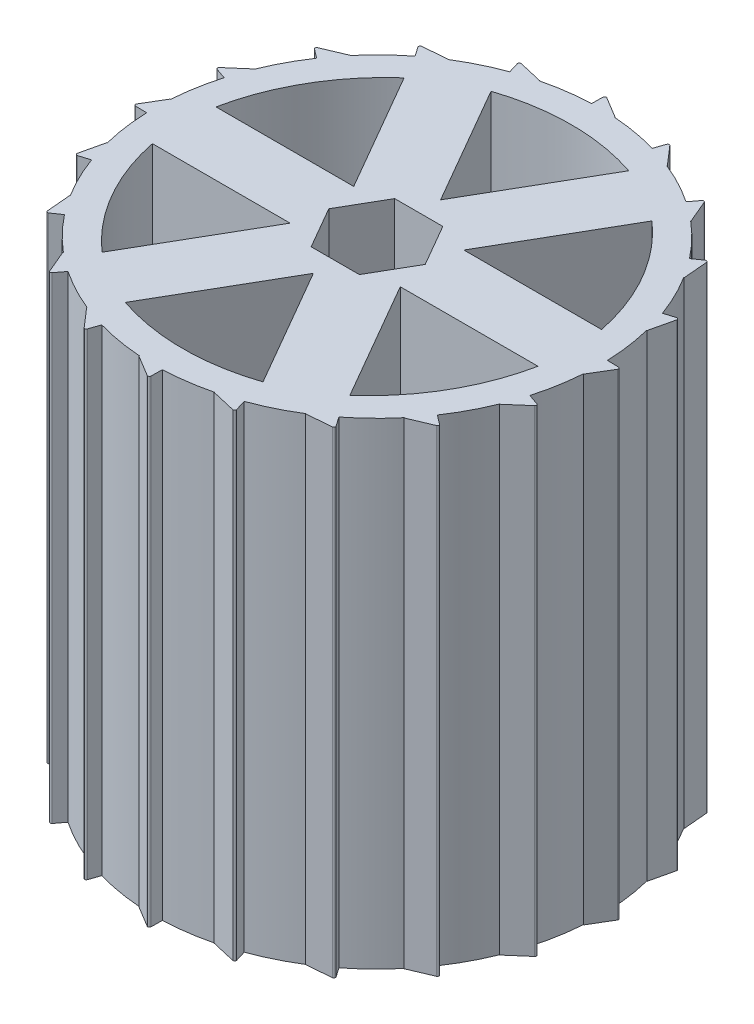
SolidWorks part; units mm, degrees
ref_plane "Front Plane" through (0, 0, 0) normal (0, 0, 1) x (1, 0, 0)
ref_plane "Top Plane" through (0, 0, 0) normal (0, 1, 0) x (1, 0, 0)
ref_plane "Right Plane" through (0, 0, 0) normal (1, 0, 0) x (0, 0, -1)
sketch "Sketch1" plane through (0, 0, 0) normal (0, 1, 0) x (1, 0, 0)
  circle A0 centre (0, 0) radius 35.56
  dimension "D1" = 71.12
extrude "Boss-Extrude1" add sketch "Sketch1" along normal blind 76.2
sketch "Sketch2" plane through (0, 76.2, 0) normal (0, 1, 0) x (1, 0, 0)
  line L7 (7.699, 0) -> (3.8495, 6.6675)
  line L8 (3.8495, 6.6675) -> (-3.8495, 6.6675)
  line L9 (-3.8495, 6.6675) -> (-7.699, 0)
  line L10 (-7.699, 0) -> (-3.8495, -6.6675)
  line L11 (-3.8495, -6.6675) -> (3.8495, -6.6675)
  line L12 (3.8495, -6.6675) -> (7.699, 0)
  circle A0 centre (0, 0) radius 6.6675 construction
extrude "Cut-Extrude1" cut sketch "Sketch2" against normal blind 76.2
sketch "Sketch3" plane through (0, 76.2, 0) normal (0, 1, 0) x (1, 0, 0)
  line L0 (8.7988, 5.08) -> (30.7959, 5.08)
  line L1 (0, 10.16) -> (10.9985, 29.21)
  line L3 (-10.9985, 29.21) -> (0, 10.16)
  line L4 (0, 29.21) -> (-10.9985, 29.21) [skipped]
  line L5 (19.7973, 24.13) -> (8.7988, 5.08)
  line L6 (8.7988, -5.08) -> (19.7973, -24.13)
  line L7 (30.7959, -5.08) -> (8.7988, -5.08)
  line L8 (0, -10.16) -> (-10.9985, -29.21)
  line L9 (10.9985, -29.21) -> (0, -10.16)
  line L10 (-8.7988, -5.08) -> (-30.7959, -5.08)
  line L11 (-19.7973, -24.13) -> (-8.7988, -5.08)
  line L12 (-8.7988, 5.08) -> (-19.7973, 24.13)
  line L13 (-30.7959, 5.08) -> (-8.7988, 5.08)
  arc A1 (-10.9985, 29.21) -> (10.9985, 29.21) centre (0, -3.503) cw
  arc A2 (19.7973, 24.13) -> (30.7959, 5.08) centre (-3.0337, -1.7515) cw
  arc A3 (30.7959, -5.08) -> (19.7973, -24.13) centre (-3.0337, 1.7515) cw
  arc A4 (10.9985, -29.21) -> (-10.9985, -29.21) centre (0, 3.503) cw
  arc A5 (-19.7973, -24.13) -> (-30.7959, -5.08) centre (3.0337, 1.7515) cw
  arc A6 (-30.7959, 5.08) -> (-19.7973, 24.13) centre (3.0337, -1.7515) cw
  point P30 (0, 0)
  dimension "D1" = 6
  dimension "D2" = 0
  dimension "D3" = 10.16
extrude "Cut-Extrude2" cut sketch "Sketch3" against normal blind 76.2
sketch "Sketch4" plane through (0, 76.2, 0) normal (0, 1, 0) x (1, 0, 0)
  line L0 (10.5069, 36.3135) -> (9.0697, 32.1554)
  line L1 (2.5396, 35.5127) -> (-1.2288, 37.783)
  line L2 (-1.2288, 37.783) -> (-1.3108, 33.3843)
  line L3 (-1.3108, 33.3843) -> (2.5396, 35.5127)
  line L4 (9.0697, 32.1554) -> (13.3893, 32.9898)
  line L5 (13.3893, 32.9898) -> (10.5069, 36.3135)
  line L6 (21.2142, 31.2893) -> (18.5624, 27.7789)
  line L7 (18.5624, 27.7789) -> (22.9284, 27.2377)
  line L8 (22.9284, 27.2377) -> (21.2142, 31.2893)
  line L9 (29.8448, 23.2024) -> (26.2381, 20.6832)
  line L10 (26.2381, 20.6832) -> (30.2231, 18.8193)
  line L11 (30.2231, 18.8193) -> (29.8448, 23.2024)
  line L12 (35.554, 12.8442) -> (31.3453, 11.5629)
  line L13 (31.3453, 11.5629) -> (34.5593, 8.5588)
  line L14 (34.5593, 8.5588) -> (35.554, 12.8442)
  line L15 (37.783, 1.2288) -> (33.3843, 1.3108)
  line L16 (33.3843, 1.3108) -> (35.5127, -2.5396)
  line L17 (35.5127, -2.5396) -> (37.783, 1.2288)
  line L18 (36.3135, -10.5069) -> (32.1554, -9.0697)
  line L19 (32.1554, -9.0697) -> (32.9898, -13.3893)
  line L20 (32.9898, -13.3893) -> (36.3135, -10.5069)
  line L21 (31.2893, -21.2142) -> (27.7789, -18.5624)
  line L22 (27.7789, -18.5624) -> (27.2377, -22.9284)
  line L23 (27.2377, -22.9284) -> (31.2893, -21.2142)
  line L24 (23.2024, -29.8448) -> (20.6832, -26.2381)
  line L25 (20.6832, -26.2381) -> (18.8193, -30.2231)
  line L26 (18.8193, -30.2231) -> (23.2024, -29.8448)
  line L27 (12.8442, -35.554) -> (11.5629, -31.3453)
  line L28 (11.5629, -31.3453) -> (8.5588, -34.5593)
  line L29 (8.5588, -34.5593) -> (12.8442, -35.554)
  line L30 (1.2288, -37.783) -> (1.3108, -33.3843)
  line L31 (1.3108, -33.3843) -> (-2.5396, -35.5127)
  line L32 (-2.5396, -35.5127) -> (1.2288, -37.783)
  line L33 (-10.5069, -36.3135) -> (-9.0697, -32.1554)
  line L34 (-9.0697, -32.1554) -> (-13.3893, -32.9898)
  line L35 (-13.3893, -32.9898) -> (-10.5069, -36.3135)
  line L36 (-21.2142, -31.2893) -> (-18.5624, -27.7789)
  line L37 (-18.5624, -27.7789) -> (-22.9284, -27.2377)
  line L38 (-22.9284, -27.2377) -> (-21.2142, -31.2893)
  line L39 (-29.8448, -23.2024) -> (-26.2381, -20.6832)
  line L40 (-26.2381, -20.6832) -> (-30.2231, -18.8193)
  line L41 (-30.2231, -18.8193) -> (-29.8448, -23.2024)
  line L42 (-35.554, -12.8442) -> (-31.3453, -11.5629)
  line L43 (-31.3453, -11.5629) -> (-34.5593, -8.5588)
  line L44 (-34.5593, -8.5588) -> (-35.554, -12.8442)
  line L45 (-37.783, -1.2288) -> (-33.3843, -1.3108)
  line L46 (-33.3843, -1.3108) -> (-35.5127, 2.5396)
  line L47 (-35.5127, 2.5396) -> (-37.783, -1.2288)
  line L48 (-36.3135, 10.5069) -> (-32.1554, 9.0697)
  line L49 (-32.1554, 9.0697) -> (-32.9898, 13.3893)
  line L50 (-32.9898, 13.3893) -> (-36.3135, 10.5069)
  line L51 (-31.2893, 21.2142) -> (-27.7789, 18.5624)
  line L52 (-27.7789, 18.5624) -> (-27.2377, 22.9284)
  line L53 (-27.2377, 22.9284) -> (-31.2893, 21.2142)
  line L54 (-23.2024, 29.8448) -> (-20.6832, 26.2381)
  line L55 (-20.6832, 26.2381) -> (-18.8193, 30.2231)
  line L56 (-18.8193, 30.2231) -> (-23.2024, 29.8448)
  line L57 (-12.8442, 35.554) -> (-11.5629, 31.3453)
  line L58 (-11.5629, 31.3453) -> (-8.5588, 34.5593)
  line L59 (-8.5588, 34.5593) -> (-12.8442, 35.554)
  circle A0 centre (0, 35.56) radius 1.27 construction
  circle A1 centre (0, 0) radius 35.56 construction
  point P67 (0, 0)
  dimension "D1" = 20
extrude "Boss-Extrude2" add sketch "Sketch4" against normal blind 76.2
fillet "Fillet1" radius 0.254 20 edges at (-31.2893, 38.1, -21.2142) (-23.2024, 38.1, -29.8448) (-12.8442, 38.1, -35.554) (-1.2288, 38.1, -37.783) (10.5069, 38.1, -36.3135) (21.2142, 38.1, -31.2893) (29.8448, 38.1, -23.2024) (35.554, 38.1, -12.8442) (37.783, 38.1, -1.2288) (36.3135, 38.1, 10.5069) (31.2893, 38.1, 21.2142) (23.2024, 38.1, 29.8448) (12.8442, 38.1, 35.554) (1.2288, 38.1, 37.783) (-10.5069, 38.1, 36.3135) (-21.2142, 38.1, 31.2893) (-29.8448, 38.1, 23.2024) (-35.554, 38.1, 12.8442) (-37.783, 38.1, 1.2288) (-36.3135, 38.1, -10.5069)
